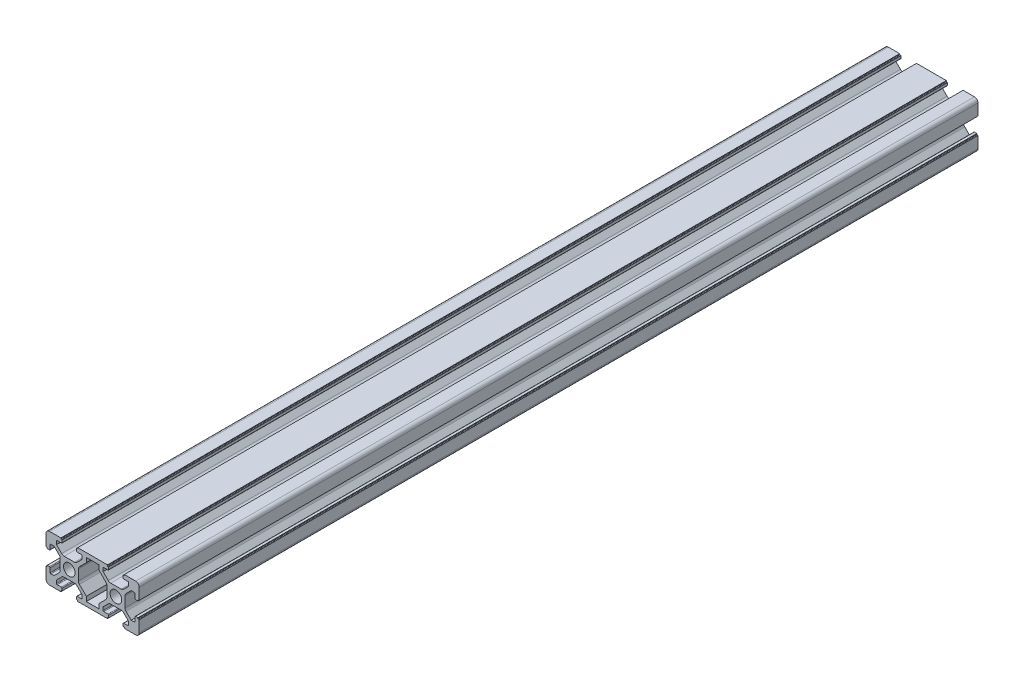
SolidWorks part; units mm, degrees
ref_plane "前视基准面" through (0, 0, 0) normal (0, 0, 1) x (1, 0, 0)
ref_plane "上视基准面" through (0, 0, 0) normal (0, 1, 0) x (1, 0, 0)
ref_plane "右视基准面" through (0, 0, 0) normal (1, 0, 0) x (0, 0, -1)
sketch "草图1" plane through (0, 0, 0) normal (0, 0, 1) x (1, 0, 0)
  line L0 (-1.9716, -6.6942) -> (-4.9322, -3.7335)
  line L1 (-5.3716, -2.6729) -> (-5.3716, 1.7645)
  line L2 (-4.9322, 2.8251) -> (-1.9716, 5.7858)
  line L3 (-0.7716, 9.5458) -> (-5.6716, 9.5458)
  line L4 (-5.6716, 9.5458) -> (-5.6716, 9.2458)
  line L5 (-5.8716, 9.0458) -> (-6.1716, 9.0458)
  line L6 (-6.1716, 9.0458) -> (-6.1716, 8.0458)
  line L7 (-5.8716, 7.7458) -> (-4.0716, 7.7458)
  line L8 (-3.7716, 7.4458) -> (-3.7716, 6.1058)
  line L9 (-3.7716, 6.1058) -> (-5.9922, 3.8851)
  line L10 (-7.0529, 3.4458) -> (-11.4903, 3.4458)
  line L11 (-12.5509, 3.8851) -> (-14.7716, 6.1058)
  line L12 (-14.7716, 6.1058) -> (-14.7716, 7.4458)
  line L13 (-14.4716, 7.7458) -> (-12.6716, 7.7458)
  line L14 (-12.3716, 8.0458) -> (-12.3716, 9.0458)
  line L15 (-12.3716, 9.0458) -> (-12.6716, 9.0458)
  line L16 (-12.8716, 9.2458) -> (-12.8716, 9.5458)
  line L17 (-12.8716, 9.5458) -> (-17.7716, 9.5458)
  line L18 (-19.2716, 8.0458) -> (-19.2716, 3.1458)
  line L19 (-19.2716, 3.1458) -> (-18.9716, 3.1458)
  line L20 (-18.7716, 2.9458) -> (-18.7716, 2.6458)
  line L21 (-18.7716, 2.6458) -> (-17.7716, 2.6458)
  line L22 (-17.4716, 2.9458) -> (-17.4716, 4.7458)
  line L23 (-17.1716, 5.0458) -> (-15.8316, 5.0458)
  line L24 (-15.8316, 5.0458) -> (-13.6109, 2.8251)
  line L25 (-13.1716, 1.7645) -> (-13.1716, -2.6729)
  line L26 (-13.6109, -3.7335) -> (-15.8316, -5.9542)
  line L27 (-15.8316, -5.9542) -> (-17.1716, -5.9542)
  line L28 (-17.4716, -5.6542) -> (-17.4716, -3.8542)
  line L29 (-17.7716, -3.5542) -> (-18.7716, -3.5542)
  line L30 (-18.7716, -3.5542) -> (-18.7716, -3.8542)
  line L31 (-18.9716, -4.0542) -> (-19.2716, -4.0542)
  line L32 (-19.2716, -4.0542) -> (-19.2716, -8.9542)
  line L33 (-17.7716, -10.4542) -> (-12.8716, -10.4542)
  line L34 (-12.8716, -10.4542) -> (-12.8716, -10.1542)
  line L35 (-12.6716, -9.9542) -> (-12.3716, -9.9542)
  line L36 (-12.3716, -9.9542) -> (-12.3716, -8.9542)
  line L37 (-12.6716, -8.6542) -> (-14.4716, -8.6542)
  line L38 (-14.7716, -8.3542) -> (-14.7716, -7.0142)
  line L39 (-14.7716, -7.0142) -> (-12.5509, -4.7935)
  line L40 (-11.4903, -4.3542) -> (-7.0529, -4.3542)
  line L41 (-5.9922, -4.7935) -> (-3.7716, -7.0142)
  line L42 (-3.7716, -7.0142) -> (-3.7716, -8.3542)
  line L43 (-4.0716, -8.6542) -> (-5.8716, -8.6542)
  line L44 (-6.1716, -8.9542) -> (-6.1716, -9.9542)
  line L45 (-6.1716, -9.9542) -> (-5.8716, -9.9542)
  line L46 (-5.6716, -10.1542) -> (-5.6716, -10.4542)
  line L47 (-5.6716, -10.4542) -> (-0.7716, -10.4542)
  line L48 (-0.7716, -10.4542) -> (7.1284, -10.4542)
  line L49 (7.1284, -10.4542) -> (7.1284, -10.1542)
  line L50 (7.3284, -9.9542) -> (7.6284, -9.9542)
  line L51 (7.6284, -9.9542) -> (7.6284, -8.9542)
  line L52 (7.3284, -8.6542) -> (5.5284, -8.6542)
  line L53 (5.2284, -8.3542) -> (5.2284, -7.0142)
  line L54 (5.2284, -7.0142) -> (7.4491, -4.7935)
  line L55 (8.5097, -4.3542) -> (12.9471, -4.3542)
  line L56 (14.0078, -4.7935) -> (16.2284, -7.0142)
  line L57 (16.2284, -7.0142) -> (16.2284, -8.3542)
  line L58 (15.9284, -8.6542) -> (14.1284, -8.6542)
  line L59 (13.8284, -8.9542) -> (13.8284, -9.9542)
  line L60 (13.8284, -9.9542) -> (14.1284, -9.9542)
  line L61 (14.3284, -10.1542) -> (14.3284, -10.4542)
  line L62 (14.3284, -10.4542) -> (19.2284, -10.4542)
  line L63 (20.7284, -8.9542) -> (20.7284, -4.0542)
  line L64 (20.7284, -4.0542) -> (20.4284, -4.0542)
  line L65 (20.2284, -3.8542) -> (20.2284, -3.5542)
  line L66 (20.2284, -3.5542) -> (19.2284, -3.5542)
  line L67 (18.9284, -3.8542) -> (18.9284, -5.6542)
  line L68 (18.6284, -5.9542) -> (17.2884, -5.9542)
  line L69 (17.2884, -5.9542) -> (15.0678, -3.7335)
  line L70 (14.6284, -2.6729) -> (14.6284, 1.7645)
  line L71 (15.0678, 2.8251) -> (17.2884, 5.0458)
  line L72 (17.2884, 5.0458) -> (18.6284, 5.0458)
  line L73 (18.9284, 4.7458) -> (18.9284, 2.9458)
  line L74 (19.2284, 2.6458) -> (20.2284, 2.6458)
  line L75 (20.2284, 2.6458) -> (20.2284, 2.9458)
  line L76 (20.4284, 3.1458) -> (20.7284, 3.1458)
  line L77 (20.7284, 3.1458) -> (20.7284, 8.0458)
  line L78 (19.2284, 9.5458) -> (14.3284, 9.5458)
  line L79 (14.3284, 9.5458) -> (14.3284, 9.2458)
  line L80 (14.1284, 9.0458) -> (13.8284, 9.0458)
  line L81 (13.8284, 9.0458) -> (13.8284, 8.0458)
  line L82 (14.1284, 7.7458) -> (15.9284, 7.7458)
  line L83 (16.2284, 7.4458) -> (16.2284, 6.1058)
  line L84 (16.2284, 6.1058) -> (14.0078, 3.8851)
  line L85 (12.9471, 3.4458) -> (8.5097, 3.4458)
  line L86 (7.4491, 3.8851) -> (5.2284, 6.1058)
  line L87 (5.2284, 6.1058) -> (5.2284, 7.4458)
  line L88 (5.5284, 7.7458) -> (7.3284, 7.7458)
  line L89 (7.6284, 8.0458) -> (7.6284, 9.0458)
  line L90 (7.6284, 9.0458) -> (7.3284, 9.0458)
  line L91 (7.1284, 9.2458) -> (7.1284, 9.5458)
  line L92 (7.1284, 9.5458) -> (2.2284, 9.5458)
  line L93 (3.4284, 5.7858) -> (6.3891, 2.8251)
  line L94 (6.8284, 1.7645) -> (6.8284, -2.6729)
  line L95 (6.3891, -3.7335) -> (3.4284, -6.6942)
  line L96 (-0.7716, 9.5458) -> (2.2284, 9.5458)
  line L99 (-1.9716, 7.7458) -> (3.4284, 7.7458)
  line L100 (3.4284, 7.7458) -> (3.4284, 5.7858)
  line L101 (-1.9716, 7.7458) -> (-1.9716, 5.7858)
  line L102 (-1.9716, -8.6542) -> (3.4284, -8.6542)
  line L103 (3.4284, -8.6542) -> (3.4284, -6.6942)
  line L104 (-1.9716, -8.6542) -> (-1.9716, -6.6942)
  arc A1 (-5.3716, -2.6729) -> (-4.9322, -3.7335) centre (-3.8716, -2.6729) ccw
  arc A2 (-4.9322, 2.8251) -> (-5.3716, 1.7645) centre (-3.8716, 1.7645) ccw
  arc A3 (-5.8716, 9.0458) -> (-5.6716, 9.2458) centre (-5.8716, 9.2458) ccw
  arc A4 (-6.1716, 8.0458) -> (-5.8716, 7.7458) centre (-5.8716, 8.0458) ccw
  arc A5 (-3.7716, 7.4458) -> (-4.0716, 7.7458) centre (-4.0716, 7.4458) ccw
  arc A6 (-7.0529, 3.4458) -> (-5.9922, 3.8851) centre (-7.0529, 4.9458) ccw
  arc A7 (-12.5509, 3.8851) -> (-11.4903, 3.4458) centre (-11.4903, 4.9458) ccw
  arc A8 (-14.4716, 7.7458) -> (-14.7716, 7.4458) centre (-14.4716, 7.4458) ccw
  arc A9 (-12.6716, 7.7458) -> (-12.3716, 8.0458) centre (-12.6716, 8.0458) ccw
  arc A10 (-12.8716, 9.2458) -> (-12.6716, 9.0458) centre (-12.6716, 9.2458) ccw
  arc A11 (-17.7716, 9.5458) -> (-19.2716, 8.0458) centre (-17.7716, 8.0458) ccw
  arc A12 (-18.7716, 2.9458) -> (-18.9716, 3.1458) centre (-18.9716, 2.9458) ccw
  arc A13 (-17.7716, 2.6458) -> (-17.4716, 2.9458) centre (-17.7716, 2.9458) ccw
  arc A14 (-17.1716, 5.0458) -> (-17.4716, 4.7458) centre (-17.1716, 4.7458) ccw
  arc A15 (-13.1716, 1.7645) -> (-13.6109, 2.8251) centre (-14.6716, 1.7645) ccw
  arc A16 (-13.6109, -3.7335) -> (-13.1716, -2.6729) centre (-14.6716, -2.6729) ccw
  arc A17 (-17.4716, -5.6542) -> (-17.1716, -5.9542) centre (-17.1716, -5.6542) ccw
  arc A18 (-17.4716, -3.8542) -> (-17.7716, -3.5542) centre (-17.7716, -3.8542) ccw
  arc A19 (-18.9716, -4.0542) -> (-18.7716, -3.8542) centre (-18.9716, -3.8542) ccw
  arc A20 (-19.2716, -8.9542) -> (-17.7716, -10.4542) centre (-17.7716, -8.9542) ccw
  arc A21 (-12.6716, -9.9542) -> (-12.8716, -10.1542) centre (-12.6716, -10.1542) ccw
  arc A22 (-12.3716, -8.9542) -> (-12.6716, -8.6542) centre (-12.6716, -8.9542) ccw
  arc A23 (-14.7716, -8.3542) -> (-14.4716, -8.6542) centre (-14.4716, -8.3542) ccw
  arc A24 (-11.4903, -4.3542) -> (-12.5509, -4.7935) centre (-11.4903, -5.8542) ccw
  arc A25 (-5.9922, -4.7935) -> (-7.0529, -4.3542) centre (-7.0529, -5.8542) ccw
  arc A26 (-4.0716, -8.6542) -> (-3.7716, -8.3542) centre (-4.0716, -8.3542) ccw
  arc A27 (-5.8716, -8.6542) -> (-6.1716, -8.9542) centre (-5.8716, -8.9542) ccw
  arc A28 (-5.6716, -10.1542) -> (-5.8716, -9.9542) centre (-5.8716, -10.1542) ccw
  arc A29 (7.3284, -9.9542) -> (7.1284, -10.1542) centre (7.3284, -10.1542) ccw
  arc A30 (7.6284, -8.9542) -> (7.3284, -8.6542) centre (7.3284, -8.9542) ccw
  arc A31 (5.2284, -8.3542) -> (5.5284, -8.6542) centre (5.5284, -8.3542) ccw
  arc A32 (8.5097, -4.3542) -> (7.4491, -4.7935) centre (8.5097, -5.8542) ccw
  arc A33 (14.0078, -4.7935) -> (12.9471, -4.3542) centre (12.9471, -5.8542) ccw
  arc A34 (15.9284, -8.6542) -> (16.2284, -8.3542) centre (15.9284, -8.3542) ccw
  arc A35 (14.1284, -8.6542) -> (13.8284, -8.9542) centre (14.1284, -8.9542) ccw
  arc A36 (14.3284, -10.1542) -> (14.1284, -9.9542) centre (14.1284, -10.1542) ccw
  arc A37 (19.2284, -10.4542) -> (20.7284, -8.9542) centre (19.2284, -8.9542) ccw
  arc A38 (20.2284, -3.8542) -> (20.4284, -4.0542) centre (20.4284, -3.8542) ccw
  arc A39 (19.2284, -3.5542) -> (18.9284, -3.8542) centre (19.2284, -3.8542) ccw
  arc A40 (18.6284, -5.9542) -> (18.9284, -5.6542) centre (18.6284, -5.6542) ccw
  arc A41 (14.6284, -2.6729) -> (15.0678, -3.7335) centre (16.1284, -2.6729) ccw
  arc A42 (15.0678, 2.8251) -> (14.6284, 1.7645) centre (16.1284, 1.7645) ccw
  arc A43 (18.9284, 4.7458) -> (18.6284, 5.0458) centre (18.6284, 4.7458) ccw
  arc A44 (18.9284, 2.9458) -> (19.2284, 2.6458) centre (19.2284, 2.9458) ccw
  arc A45 (20.4284, 3.1458) -> (20.2284, 2.9458) centre (20.4284, 2.9458) ccw
  arc A46 (20.7284, 8.0458) -> (19.2284, 9.5458) centre (19.2284, 8.0458) ccw
  arc A47 (14.1284, 9.0458) -> (14.3284, 9.2458) centre (14.1284, 9.2458) ccw
  arc A48 (13.8284, 8.0458) -> (14.1284, 7.7458) centre (14.1284, 8.0458) ccw
  arc A49 (16.2284, 7.4458) -> (15.9284, 7.7458) centre (15.9284, 7.4458) ccw
  arc A50 (12.9471, 3.4458) -> (14.0078, 3.8851) centre (12.9471, 4.9458) ccw
  arc A51 (7.4491, 3.8851) -> (8.5097, 3.4458) centre (8.5097, 4.9458) ccw
  arc A52 (5.5284, 7.7458) -> (5.2284, 7.4458) centre (5.5284, 7.4458) ccw
  arc A53 (7.3284, 7.7458) -> (7.6284, 8.0458) centre (7.3284, 8.0458) ccw
  arc A54 (7.1284, 9.2458) -> (7.3284, 9.0458) centre (7.3284, 9.2458) ccw
  arc A55 (6.8284, 1.7645) -> (6.3891, 2.8251) centre (5.3284, 1.7645) ccw
  arc A56 (6.3891, -3.7335) -> (6.8284, -2.6729) centre (5.3284, -2.6729) ccw
  circle A58 centre (10.7284, -0.4542) radius 2.5
  circle A63 centre (-9.2716, -0.4542) radius 2.5
extrude "凸台-拉伸1" add sketch "草图1" along normal blind 360
